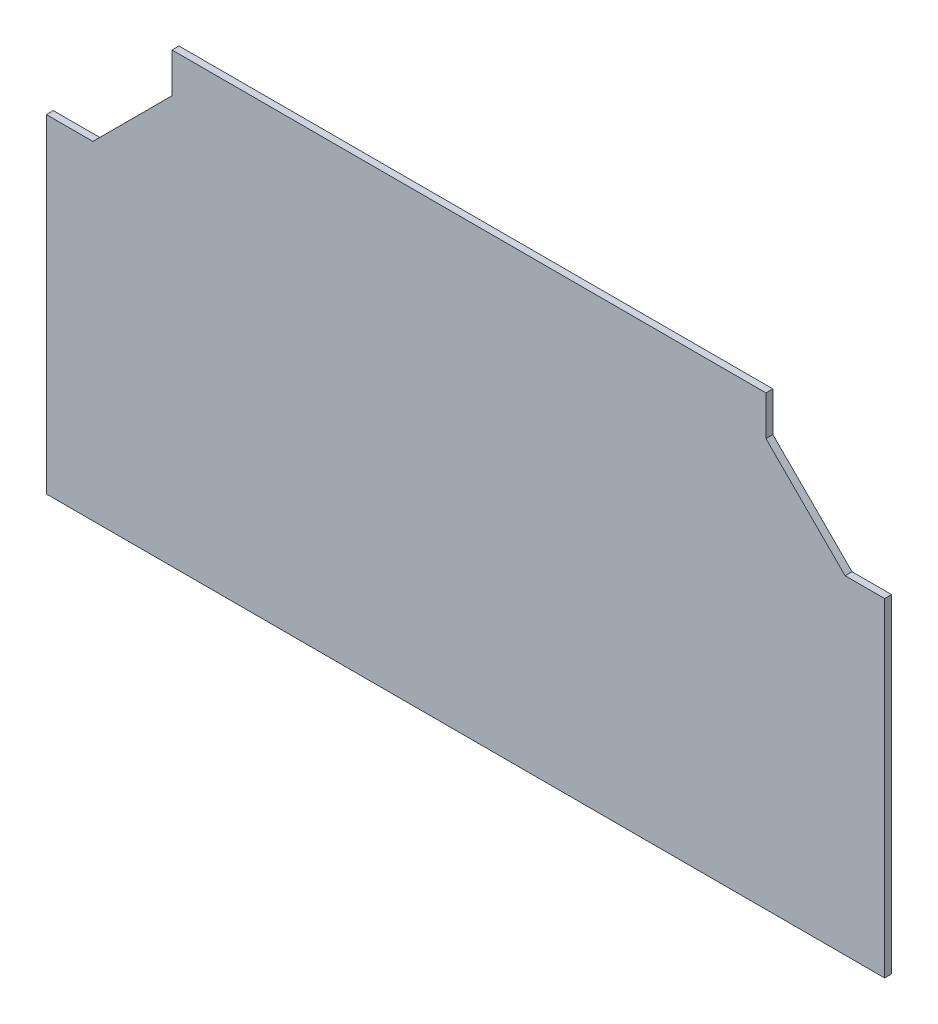
SolidWorks part; units mm, degrees
ref_plane "Front Plane" through (0, 0, 0) normal (0, 0, 1) x (1, 0, 0)
ref_plane "Top Plane" through (0, 0, 0) normal (0, 1, 0) x (1, 0, 0)
ref_plane "Right Plane" through (0, 0, 0) normal (1, 0, 0) x (0, 0, -1)
sketch "Sketch1" plane through (0, 0, 0) normal (0, 0, 1) x (1, 0, 0)
  line L0 (-420, 0) -> (-423.5, 0)
  line L1 (-60, 0) -> (-360, 0)
  line L2 (0, 6) -> (0, 166)
  line L3 (-60, 226) -> (-360, 226)
  line L4 (-423.5, 0) -> (-423.5, 166)
  line L23 (-400, 166) -> (-423.5, 166)
  line L24 (-400, 166) -> (-360, 206)
  line L25 (-360, 206) -> (-360, 226)
  line L26 (-423.5, 166) -> (-423.5, 226) construction
  line L27 (-360, 226) -> (-423.5, 226) construction
  line L28 (0, 166) -> (-20, 166)
  line L29 (-20, 166) -> (-60, 206)
  line L30 (-60, 206) -> (-60, 226)
  line L31 (-60, 226) -> (0, 226) construction
  line L32 (0, 166) -> (0, 226) construction
  line L33 (-420, 0) -> (-360, 0)
  line L34 (-60, 0) -> (0, 0)
  line L35 (0, 0) -> (0, 6)
  dimension "D3" = 226
  dimension "D4" = 423.5
  dimension "D5" = 400.2224
  dimension "D6" = 3.5
  dimension "D7" = 60
  dimension "D8" = 226
  dimension "D9" = 6
  dimension "D10" = 60
  dimension "D16" = 166
  dimension "D17" = 360
  dimension "D18" = 23.5
  dimension "D19" = 56.5685
  dimension "D20" = 300
  dimension "D21" = 166
  dimension "D22" = 20
  dimension "D23" = 56.5685
extrude "Boss-Extrude2" add sketch "Sketch1" along normal blind 3.5
